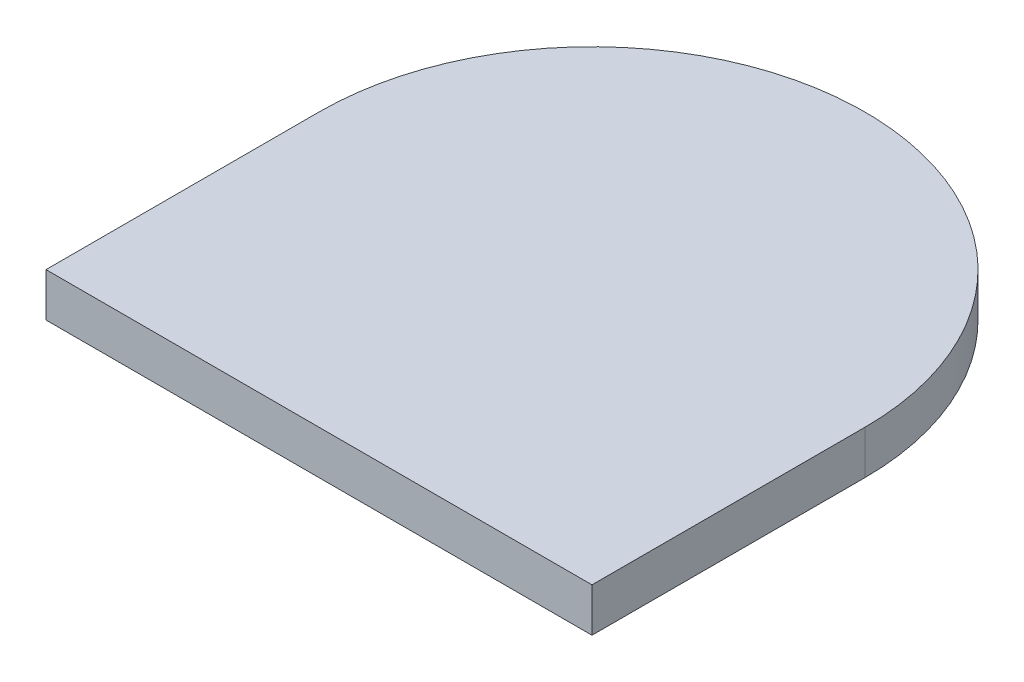
SolidWorks part; units mm, degrees
ref_plane "Front Plane" through (0, 0, 0) normal (0, 0, 1) x (1, 0, 0)
ref_plane "Top Plane" through (0, 0, 0) normal (0, 1, 0) x (1, 0, 0)
ref_plane "Right Plane" through (0, 0, 0) normal (1, 0, 0) x (0, 0, -1)
sketch "Sketch1" plane through (0, 0, 0) normal (0, 1, 0) x (1, 0, 0)
  circle A0 centre (0, 0) radius 25
  dimension "D1" = 50
extrude "Boss-Extrude1" add sketch "Sketch1" along normal blind 3
sketch "Sketch2" plane through (0, 3, 0) normal (0, 1, 0) x (1, 0, 0)
  line L1 (0, -25) -> (25, -25)
  line L2 (25, -25) -> (25, 0)
  line L4 (-25, 0) -> (-25, -25)
  line L5 (-25, -25) -> (0, -25)
  circle A0 centre (0, 0) radius 25 construction
  circle A2 centre (0, 0) radius 25
  arc A3 (25, 0) -> (-25, 0) centre (0, 0) ccw
  dimension "D1" = 0
extrude "Boss-Extrude2" add sketch "Sketch2" against normal blind 4
